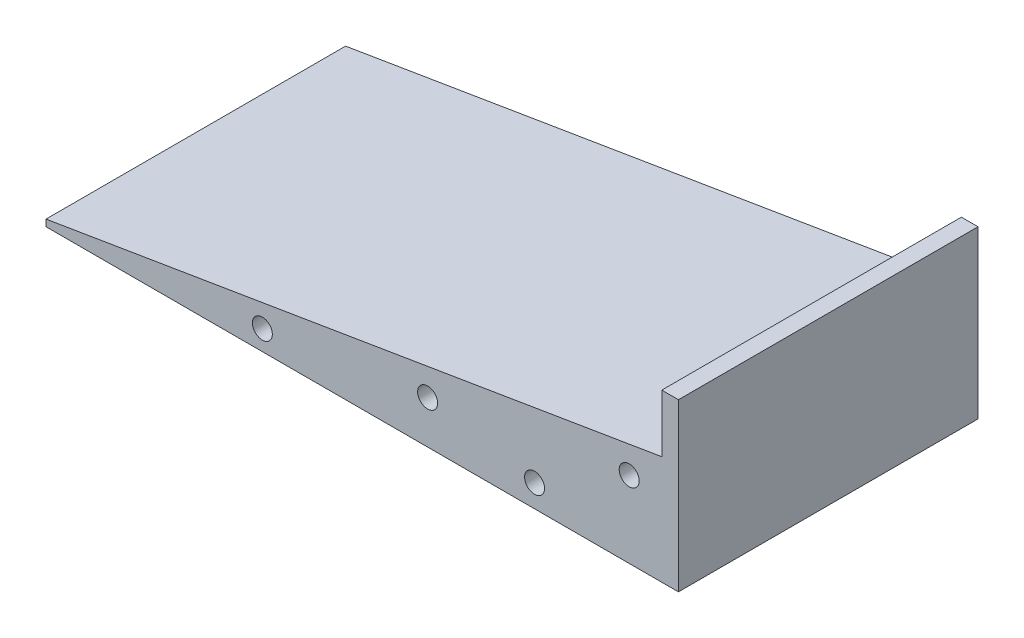
SolidWorks part; units mm, degrees
ref_plane "Plan de face" through (0, 0, 0) normal (0, 0, 1) x (1, 0, 0)
ref_plane "Plan de dessus" through (0, 0, 0) normal (0, 1, 0) x (1, 0, 0)
ref_plane "Plan de droite" through (0, 0, 0) normal (1, 0, 0) x (0, 0, -1)
sketch "Esquisse1" plane through (0, 0, 0) normal (0, 0, 1) x (1, 0, 0)
  line L0 (-105.796, 0) -> (84.204, 0)
  line L1 (84.204, 0) -> (84.204, 33.5021)
  line L2 (84.204, 25.3929) -> (-68.9493, 0) construction
  line L3 (-105.796, 0) -> (-105.796, 2)
  line L4 (-105.796, 2) -> (84.204, 33.5021)
  line L5 (40.9815, 6.7762) -> (8.8615, 12.9011) construction
  line L6 (69.406, 22.9394) -> (40.9815, 6.7762) construction
  circle A0 centre (69.406, 22.9394) radius 3
  circle A1 centre (40.9815, 6.7762) radius 3
  circle A2 centre (-40.796, 6) radius 3
  circle A3 centre (8.8615, 12.9011) radius 3
  dimension "D3" = 6
  dimension "D6" = 6
  dimension "D8" = 6
  dimension "D11" = 6
  dimension "D1" = 190
  dimension "D2" = 2
  dimension "D4" = 15
  dimension "D7" = 8
  dimension "D9" = 6
  dimension "D10" = 65
extrude "Boss.-Extru.1" add sketch "Esquisse1" along normal blind 200
sketch "Esquisse4" plane through (84.204, 0, 0) normal (1, 0, 0) x (0, 0, -1)
  line L1 (-200, 0) -> (-205, 0)
  line L2 (-200, 0) -> (-200, 50)
  line L3 (-200, 50) -> (-205, 50)
  line L4 (-205, 0) -> (-205, 50)
  line L5 (0, 0) -> (5, 0)
  line L6 (0, 0) -> (0, 50)
  line L7 (0, 50) -> (5, 50)
  line L8 (5, 0) -> (5, 50)
  dimension "D1" = 50
  dimension "D2" = 5
  dimension "D3" = 5
  dimension "D4" = 50
extrude "Boss.-Extru.4" add sketch "Esquisse4" against normal blind 180
sketch "Esquisse8" plane through (0, 50, 0) normal (0, 1, 0) x (1, 0, 0)
  line L0 (84.204, 0) -> (-95.796, 0)
  line L1 (-95.796, 0) -> (-95.796, -5)
  line L2 (-95.796, -5) -> (84.204, 0)
  dimension "D1" = 5
extrude "Boss.-Extru.7" add sketch "Esquisse8" against normal up to surface (50 mm away)
ref_plane "Plan2" through (-5.796, 0, 0) normal (1, 0, 0) x (0, 0, -1)
sketch "Esquisse6" plane through (0, 0, -5) normal (0, 0, -1) x (-1, 0, 0)
  line L1 (105.796, 0) -> (85.796, 0)
  line L2 (105.796, 0) -> (105.796, 10.7198)
  line L3 (105.796, 10.7198) -> (85.796, 10.7198)
  line L4 (85.796, 0) -> (85.796, 10.7198)
  line L5 (95.796, 0) -> (95.796, 50) construction
  dimension "D1" = 10
extrude "Enlèv. mat.-Extru.2" cut sketch "Esquisse6" against normal blind 10
ref_plane "Plan3" through (0, 0, 100) normal (0, 0, -1) x (-1, 0, 0)
sketch "Esquisse5" plane through (84.204, 0, 0) normal (1, 0, 0) x (0, 0, -1)
  line L1 (-205, 0) -> (-195, 0)
  line L2 (-205, 0) -> (-205, 10)
  line L3 (-205, 10) -> (-195, 10)
  line L4 (-195, 0) -> (-195, 10)
  line L5 (5, 0) -> (-5, 0)
  line L6 (5, 0) -> (5, 10)
  line L7 (5, 10) -> (-5, 10)
  line L8 (-5, 0) -> (-5, 10)
  dimension "D1" = 10
  dimension "D2" = 10
  dimension "D3" = 10
  dimension "D4" = 10
extrude "Enlèv. mat.-Extru.1" cut sketch "Esquisse5" against normal blind 10
sketch "Esquisse14" plane through (0, 0, -5) normal (0, 0, -1) x (-1, 0, 0)
  circle A0 centre (-69.406, 22.9394) radius 5
  circle A1 centre (-40.9815, 6.7762) radius 5
  circle A2 centre (-8.8615, 12.9011) radius 5
  circle A3 centre (40.796, 6) radius 5
  dimension "D1" = 10
  dimension "D2" = 10
  dimension "D3" = 10
  dimension "D4" = 10
extrude "Enlèv. mat.-Extru.4" cut sketch "Esquisse14" against normal blind 15
mirror "Symétrie3" about plane through (0, 0, 100) normal (0, 0, -1) of "Enlèv. mat.-Extru.4", "Boss.-Extru.7", "Enlèv. mat.-Extru.2"
sketch "Esquisse15" plane through (0, 0, -5) normal (0, 0, -1) x (-1, 0, 0)
  line L0 (-84.204, 33.5021) -> (-79.204, 32.6731)
  line L1 (-84.204, 33.5021) -> (85.796, 5.316) construction
  line L2 (-79.204, 32.6731) -> (-79.204, 50)
  line L3 (95.796, 50) -> (-84.204, 50) construction
  line L4 (-79.204, 50) -> (-84.204, 50)
  line L5 (-84.204, 50) -> (-84.204, 33.5021)
  dimension "D1" = 5
extrude "Boss.-Extru.8" add sketch "Esquisse15" against normal up to surface (204.8611 mm away)
sketch "Esquisse16" plane through (0, 50, 0) normal (0, 1, 0) x (1, 0, 0)
  line L1 (-105.796, -195) -> (-105.796, -5) construction
  line L2 (84.204, -205) -> (-105.796, -205)
  line L3 (84.204, -205) -> (84.204, -145)
  line L4 (84.204, -145) -> (-105.796, -145)
  line L7 (-105.796, -205) -> (-105.796, -145)
  line L9 (84.204, 5) -> (-105.796, 5)
  line L10 (84.204, 5) -> (84.204, -55)
  line L11 (84.204, -55) -> (-105.796, -55)
  line L12 (-105.796, 5) -> (-105.796, -55)
  dimension "D1" = 60
  dimension "D2" = 60
extrude "Enlèv. mat.-Extru.5" cut sketch "Esquisse16" against normal up to surface (50 mm away) up to face at (9.5373, 0, 119.9815)
